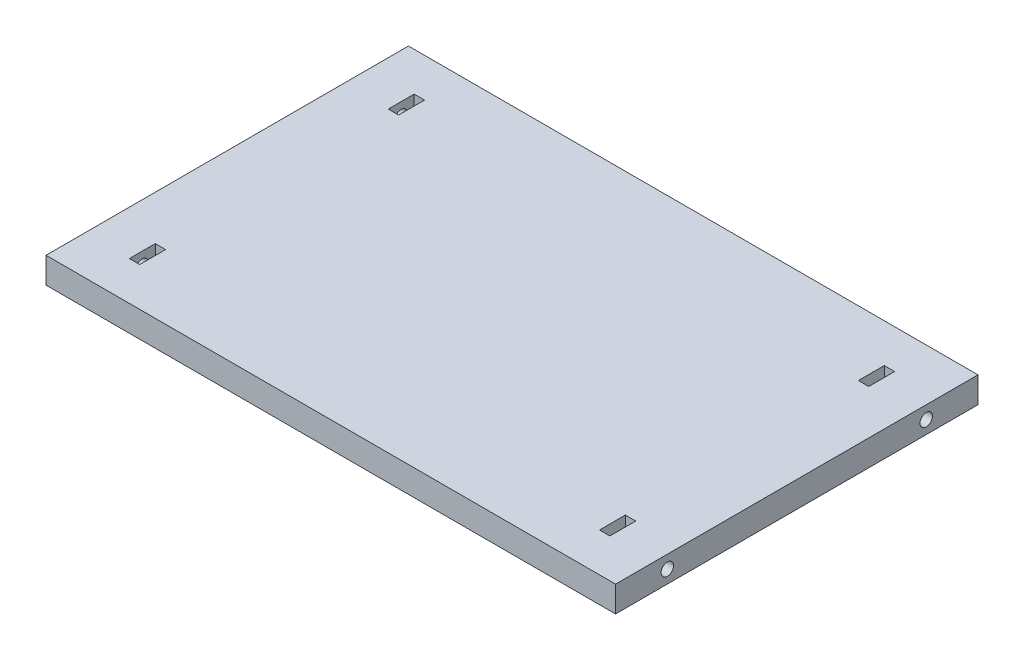
SolidWorks part; units mm, degrees
ref_plane "Front Plane" through (0, 0, 0) normal (0, 0, 1) x (1, 0, 0)
ref_plane "Top Plane" through (0, 0, 0) normal (0, 1, 0) x (1, 0, 0)
ref_plane "Right Plane" through (0, 0, 0) normal (1, 0, 0) x (0, 0, -1)
sketch "Sketch1" plane through (0, 0, 0) normal (0, 0, 1) x (1, 0, 0)
  line L0 (-55, 18.5) -> (-55, -18.5) construction
  line L1 (55, 18.5) -> (-55, 18.5)
  line L2 (55, 18.5) -> (55, 13.5)
  line L3 (55, 13.5) -> (-55, 13.5)
  line L4 (-55, 18.5) -> (-55, 13.5)
  dimension "D1" = 5
extrude "Boss-Extrude1" add sketch "Sketch1" along normal up to surface (70 mm away)
sketch "Sketch5" plane through (0, 13.5, 0) normal (0, -1, 0) x (1, 0, 0)
  line L0 (51.5061, 8.2919) -> (-45.0139, 8.2919) construction
  line L1 (47.8375, 14.2168) -> (-15.0141, 14.2168)
  line L2 (47.8375, 14.2168) -> (47.8375, 8.2919)
  line L3 (47.8375, 8.2919) -> (-15.0141, 8.2919)
  line L4 (-15.0141, 14.2168) -> (-15.0141, 8.2919)
  line L5 (-45.0139, 61.7081) -> (50.7587, 61.7081) construction
  line L6 (53.3212, 13.4167) -> (46.0197, 13.4167)
  line L7 (53.3212, 13.4167) -> (53.3212, 60.4889)
  line L8 (53.3212, 60.4889) -> (46.0197, 60.4889)
  line L9 (46.0197, 13.4167) -> (46.0197, 60.4889)
  line L10 (42.2132, 61.7081) -> (-25.4778, 61.7081)
  line L11 (42.2132, 61.7081) -> (42.2132, 57.2045)
  line L12 (42.2132, 57.2045) -> (-25.4778, 57.2045)
  line L13 (-25.4778, 61.7081) -> (-25.4778, 57.2045)
  line L14 (-25.6789, 57.0034) -> (-26.6577, 56.0246) construction
  line L16 (23.5124, 29.3054) -> (14.5135, 29.3054)
  line L17 (23.5124, 29.3054) -> (23.5124, 41.6789)
  line L18 (23.5124, 41.6789) -> (14.5135, 41.6789)
  line L19 (14.5135, 29.3054) -> (14.5135, 41.6789)
  line L20 (-15.0141, 21.2908) -> (-34.4179, 21.2908)
  line L21 (-15.0141, 21.2908) -> (-15.0141, 11.7294)
  line L22 (-15.0141, 11.7294) -> (-34.4179, 11.7294)
  line L23 (-34.4179, 21.2908) -> (-34.4179, 11.7294)
  line L24 (-43.698, 58.5518) -> (-16.7014, 58.5518)
  line L25 (-43.698, 58.5518) -> (-43.698, 9.1985)
  line L26 (-43.698, 9.1985) -> (-16.7014, 9.1985)
  line L27 (-16.7014, 58.5518) -> (-16.7014, 9.1985)
  line L28 (-2.9218, 26.9151) -> (-15.0141, 26.9151)
  line L29 (-2.9218, 26.9151) -> (-2.9218, 14.2168)
  line L30 (-2.9218, 14.2168) -> (-15.0141, 14.2168)
  line L31 (-15.0141, 26.9151) -> (-15.0141, 14.2168)
extrude "Cut-Extrude4" [suppressed] cut sketch "Sketch5" against normal blind 2 contours L6 L9 L1 L4 L3 L2 | L9 L1 L2 L6 L7 L8 | L28 L31 L21 L1 L29 | L27 L20 L23 L22 | L24 L27 L12 L11 L10 L13 | L9 L6 L2 L1
hole_wizard "M2 Clearance Hole1" positions "Sketch2" profile "Sketch3" hole size "M2" standard "ANSI Metric"
sketch "Sketch2" plane through (-55, 0, 0) normal (-1, 0, 0) x (0, 0, 1)
  line L0 (70, 13.5) -> (70, 18.5) construction
  line L1 (0, 18.5) -> (0, 13.5) construction
  line L2 (10, 18.5) -> (10, 13.5) construction
  line L3 (70, 18.5) -> (0, 18.5) construction
  line L4 (70, 13.5) -> (0, 13.5) construction
  line L6 (60, 18.5) -> (60, 13.5) construction
  point P0 (10, 16)
  point P2 (60, 16)
  dimension "D1" = 10
  dimension "D2" = 10
sketch "Sketch3" plane through (-55, 16, 10) normal (0, 1, 0) x (0, 0, 1)
  line L0 (0, 0) -> (0, 9.721)
  line L1 (0, 9.721) -> (1.2, 9)
  line L2 (1.2, 9) -> (1.2, 0)
  line L5 (1.2, 0) -> (0, 0)
  line L10 (0, 9.721) -> (-1.2, 9) construction
  line L11 (0, -6.35) -> (0, 107.95) construction
  dimension "Hole Dia." = 2.4
  dimension "Hole Depth" = 9
  dimension "Drill Angle" = 118
sketch "Sketch4" plane through (0, 18.5, 0) normal (0, 1, 0) x (1, 0, 0)
  line L0 (-55, -8.8) -> (-55, -11.2) construction
  line L1 (-44.4, -62.5) -> (-46.4, -62.5)
  line L2 (-44.4, -62.5) -> (-44.4, -57.5)
  line L3 (-44.4, -57.5) -> (-46.4, -57.5)
  line L4 (-46.4, -62.5) -> (-46.4, -57.5)
  line L5 (-44.4, -12.5) -> (-46.4, -12.5)
  line L6 (-44.4, -12.5) -> (-44.4, -7.5)
  line L7 (-44.4, -7.5) -> (-46.4, -7.5)
  line L8 (-46.4, -12.5) -> (-46.4, -7.5)
  line L9 (-55, -8.8) -> (-55, -11.2) construction
  line L10 (-55, -58.8) -> (-55, -61.2) construction
  line L11 (-55, -58.8) -> (-55, -61.2) construction
  line L13 (-56.4, -7.5) -> (-56.4, -12.5) construction
  point P12 (-55, -10)
  point P13 (-46.4, -10)
  point P14 (-55, -60)
  point P15 (-46.4, -60)
  dimension "D1" = 12
  dimension "D2" = 2
  dimension "D3" = 5
extrude "Cut-Extrude1" cut sketch "Sketch4" against normal blind 4.5
mirror "Mirror1" about plane through (0, 0, 0) normal (1, 0, 0) of "Cut-Extrude1", "M2 Clearance Hole1"
